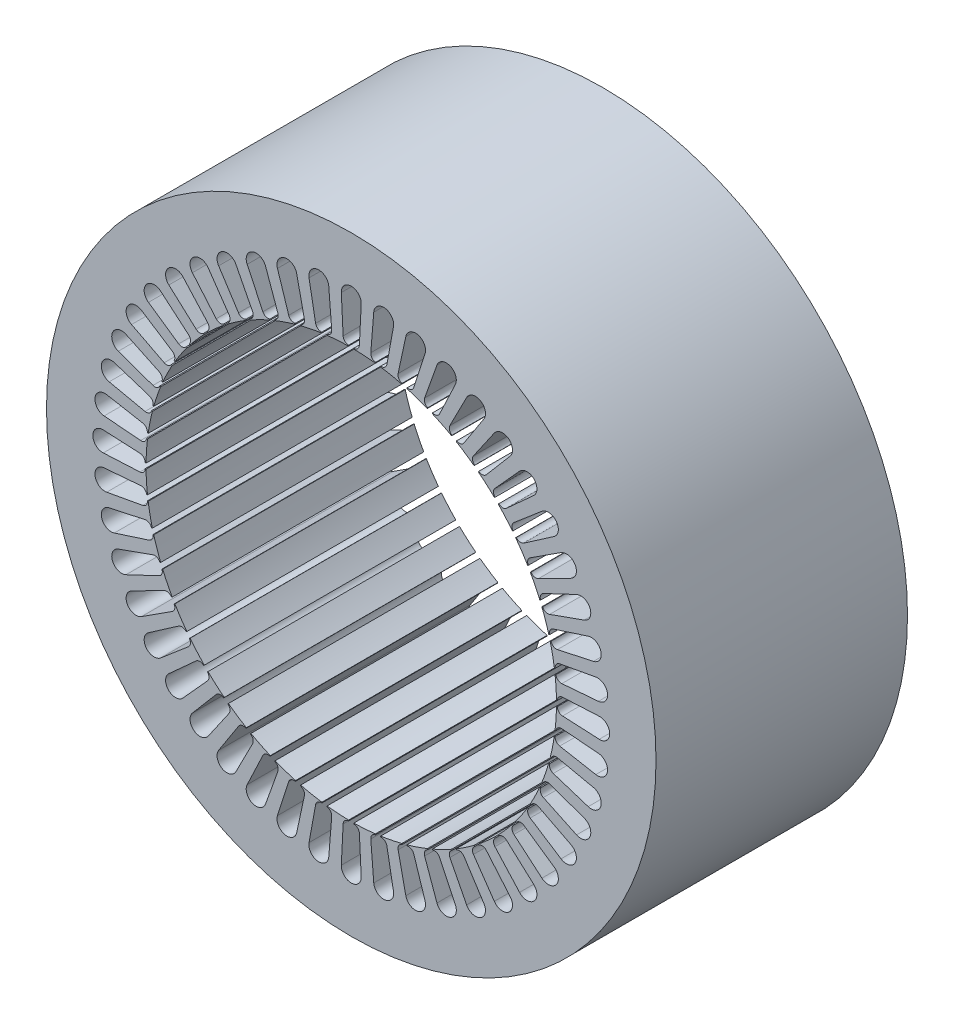
SolidWorks part; units mm, degrees
material "Ductile Iron"
ref_plane "Front Plane" through (0, 0, 0) normal (0, 0, 1) x (1, 0, 0)
ref_plane "Top Plane" through (0, 0, 0) normal (0, 1, 0) x (1, 0, 0)
ref_plane "Right Plane" through (0, 0, 0) normal (1, 0, 0) x (0, 0, -1)
sketch "Sketch1" plane through (0, 0, 0) normal (0, 0, 1) x (1, 0, 0)
  circle A0 centre (0, 0) radius 174.5
  circle A1 centre (0, 0) radius 117.5
  dimension "D1" = 349
  dimension "D2" = 235
extrude "Diameters" add sketch "Sketch1" along normal mid plane 144
sketch "Sketch2" plane through (0, 0, 72) normal (0, 0, 1) x (1, 0, 0)
  line L0 (0, 0) -> (174.5, 0) construction
  line L1 (117.4904, 1.5) -> (117.9904, 1.5)
  line L2 (120.9869, 4.65) -> (141.9869, 5.7)
  line L3 (120.9869, -4.65) -> (141.9869, -5.7)
  line L4 (117.4904, -1.5) -> (117.9904, -1.5)
  circle A0 centre (0, 0) radius 117.5 construction
  arc A1 (117.4904, -1.5) -> (117.4904, 1.5) centre (0, 0) ccw
  circle A2 centre (0, 0) radius 174.5 construction
  arc A3 (117.9904, 1.5) -> (120.9869, 4.65) centre (121.1444, 1.5) cw
  arc A4 (141.9869, 5.7) -> (147.979, 0) centre (142.2719, 0) cw
  arc A5 (141.9869, -5.7) -> (147.979, 0) centre (142.2719, 0) ccw
  arc A6 (117.9904, -1.5) -> (120.9869, -4.65) centre (121.1444, -1.5) ccw
  dimension "D1" = 3
  dimension "D2" = 9.3
  dimension "D3" = 11.4
  dimension "D4" = 0.5
  dimension "D5" = 21
extrude "Slot" cut sketch "Sketch2" against normal up to surface (144 mm away) up to face at (174.5, 0, -72)
pattern_circular "Number of Slots" count 48 over 360 about axis through (0, 0, 0) along (0, 0, 1) of "Slot"
equation "\"Do\"= 349'Stator outer diameter"
equation "\"D1@Sketch1\"=\"Do\""
equation "\"D\"= 235'Stator diameter on th airgap side"
equation "\"D2@Sketch1\"=\"D\""
equation "\"Bs0\"= 3'Stator slot opening at the slot tip"
equation "\"D1@Sketch2\"=\"Bs0\""
equation "\"Bs1\"= 9.3'Stator slot opening at the slot wedge"
equation "\"D2@Sketch2\"=\"Bs1\""
equation "\"Bs2\"= 11.4'Stator slot opening at the slot bottom"
equation "\"D3@Sketch2\"=\"Bs2\""
equation "\"Hs0\"= 0.5'Height of stator tooth tip"
equation "\"D4@Sketch2\"=\"Hs0\""
equation "\"Hs2\"= 21'Height of stator tooth from wedge to slot bottom"
equation "\"D5@Sketch2\"=\"Hs2\""
equation "\"Ns\"= 48'Number od stator slots"
equation "\"D1@Number of Slots\"=\"Ns\""
